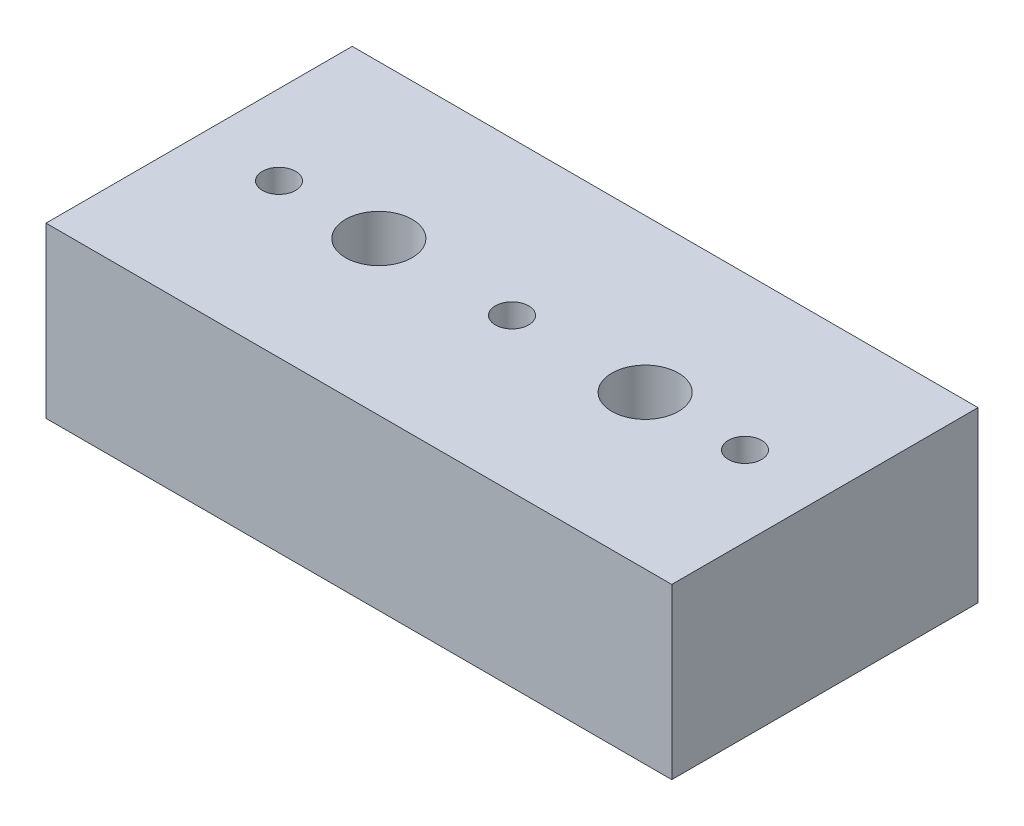
SolidWorks part; units mm, degrees
ref_plane "Front Plane" through (0, 0, 0) normal (0, 0, 1) x (1, 0, 0)
ref_plane "Top Plane" through (0, 0, 0) normal (0, 1, 0) x (1, 0, 0)
ref_plane "Right Plane" through (0, 0, 0) normal (1, 0, 0) x (0, 0, -1)
sketch "Sketch1" plane through (0, 0, 0) normal (0, 1, 0) x (1, 0, 0)
  line L0 (-17.5, 0) -> (17.5, 0) construction
  line L1 (-23.5, -11.5) -> (23.5, -11.5)
  line L2 (-23.5, -11.5) -> (-23.5, 11.5)
  line L3 (-23.5, 11.5) -> (23.5, 11.5)
  line L4 (23.5, -11.5) -> (23.5, 11.5)
  line L5 (-23.5, -11.5) -> (23.5, 11.5) construction
  line L6 (-23.5, 11.5) -> (23.5, -11.5) construction
  line L7 (-10, 0) -> (10, 0) construction
  circle A0 centre (-10, 0) radius 2.5
  circle A1 centre (10, 0) radius 2.5
  circle A2 centre (17.5, 0) radius 1.25
  circle A3 centre (0, 0) radius 1.25
  circle A4 centre (-17.5, 0) radius 1.25
  point P0 (0, 0)
  dimension "D3" = 2.5
  dimension "D4" = 5
  dimension "D1" = 47
  dimension "D2" = 23
  dimension "D5" = 35
  dimension "D6" = 20
extrude "Boss-Extrude1" add sketch "Sketch1" along normal mid plane 12.7
